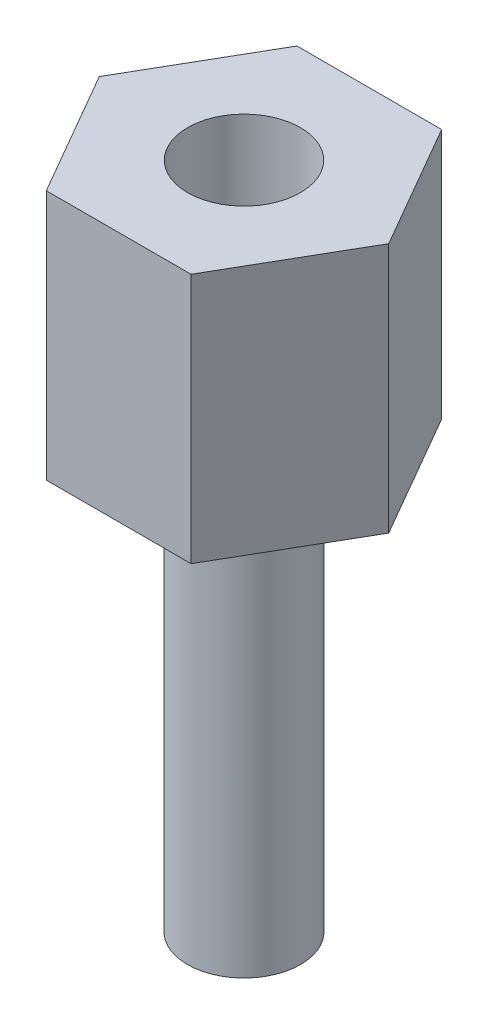
SolidWorks part; units mm, degrees
ref_plane "Front Plane" through (0, 0, 0) normal (0, 0, 1) x (1, 0, 0)
ref_plane "Top Plane" through (0, 0, 0) normal (0, 1, 0) x (1, 0, 0)
ref_plane "Right Plane" through (0, 0, 0) normal (1, 0, 0) x (0, 0, -1)
sketch "Esquisse1" plane through (0, 0, 0) normal (0, 1, 0) x (1, 0, 0)
  line L1 (3.4641, 0) -> (1.7321, 3)
  line L2 (1.7321, 3) -> (-1.7321, 3)
  line L3 (-1.7321, 3) -> (-3.4641, 0)
  line L4 (-3.4641, 0) -> (-1.7321, -3)
  line L5 (-1.7321, -3) -> (1.7321, -3)
  line L6 (1.7321, -3) -> (3.4641, 0)
  circle A0 centre (0, 0) radius 3 construction
extrude "Boss.-Extru.1" add sketch "Esquisse1" along normal blind 6
sketch "Esquisse2" plane through (0, 0, 0) normal (0, -1, 0) x (1, 0, 0)
  circle A0 centre (0, 0) radius 1.3538
extrude "Boss.-Extru.2" add sketch "Esquisse2" along normal blind 10
sketch "Esquisse3" plane through (0, 6, 0) normal (0, 1, 0) x (1, 0, 0)
  circle A0 centre (0, 0) radius 1.35
extrude "Enlèv. mat.-Extru.1" cut sketch "Esquisse3" against normal blind 5
